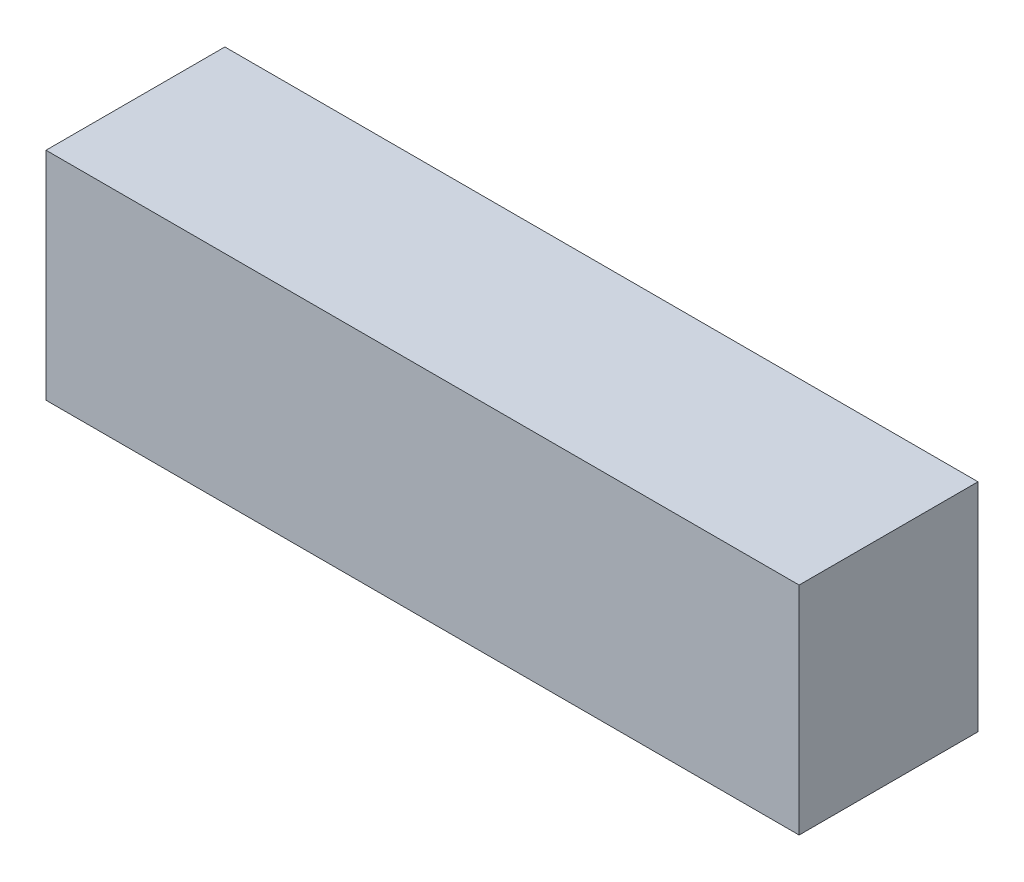
SolidWorks part; units mm, degrees
ref_plane "Front Plane" through (0, 0, 0) normal (0, 0, 1) x (1, 0, 0)
ref_plane "Top Plane" through (0, 0, 0) normal (0, 1, 0) x (1, 0, 0)
ref_plane "Right Plane" through (0, 0, 0) normal (1, 0, 0) x (0, 0, -1)
sketch "Sketch1" plane through (0, 0, 0) normal (0, 0, 1) x (1, 0, 0)
  line L1 (0, 0) -> (40, 0)
  line L2 (0, 0) -> (0, 11.5)
  line L3 (0, 11.5) -> (40, 11.5)
  line L4 (40, 0) -> (40, 11.5)
  dimension "D1" = 40
  dimension "D2" = 11.5
extrude "Boss-Extrude1" add sketch "Sketch1" along normal blind 9.5
